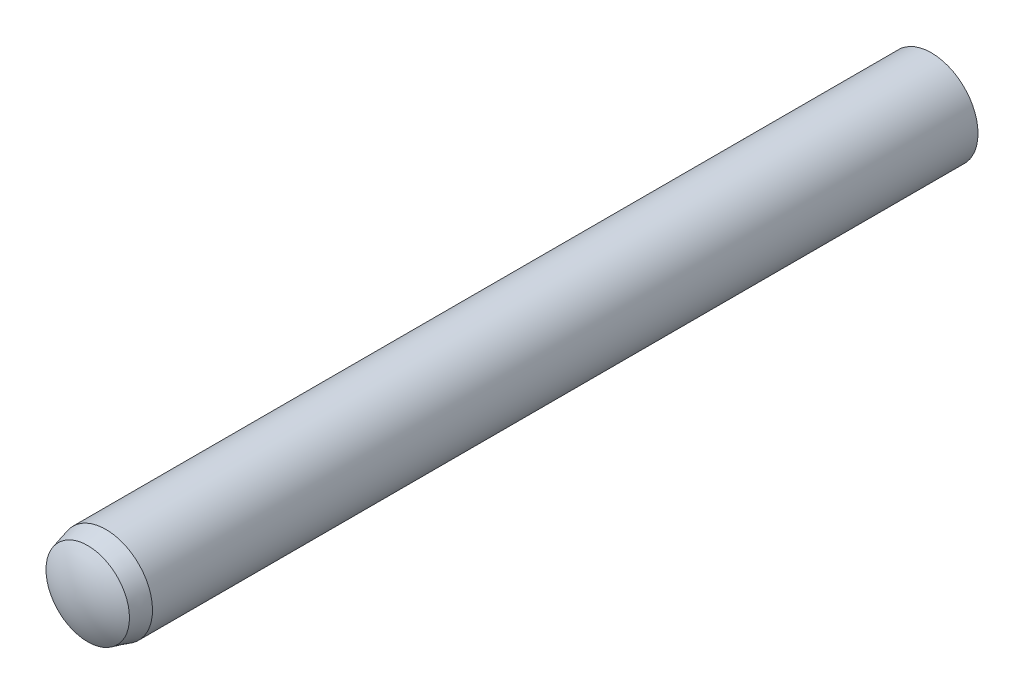
SolidWorks part; units mm, degrees
ref_plane "Front Plane" through (0, 0, 0) normal (0, 0, 1) x (1, 0, 0)
ref_plane "Top Plane" through (0, 0, 0) normal (0, 1, 0) x (1, 0, 0)
ref_plane "Right Plane" through (0, 0, 0) normal (1, 0, 0) x (0, 0, -1)
sketch "Sketch1" plane through (0, 0, 0) normal (0, 0, 1) x (1, 0, 0)
  circle A0 centre (0, 0) radius 1.5
  point P3 (0, 1.5)
  dimension "Diameter" = 3
sketch "Sketch2" plane through (0, 0, 0) normal (1, 0, 0) x (0, 0, -1)
  line L0 (-14, 0) -> (14, 0) construction
  line L1 (-14, 0) -> (-14, 1.5) construction
  line L2 (-14, 1.5) -> (14, 1.5)
  line L3 (14, 1.5) -> (14, 0) construction
  line L4 (-13.61, 1.3432) -> (-13.025, 1.5)
  arc A0 (-14, 0) -> (-13.61, 1.3432) centre (-11.4918, 0) cw
  arc A1 (14, 0) -> (13.55, 1.5) centre (11.275, 0) ccw
  point P2 (0, 0)
  point P11 (-11, 0)
  point P13 (11, 0)
  dimension "Length" = 28
  dimension "D1" = 15
  dimension "D2" = 0.45
  dimension "D3" = 0.975
  dimension "D4" = 0.585
  dimension "D5" = 3
  dimension "D6" = 3
sketch "Sketch3" plane through (0, 0, 0) normal (1, 0, 0) x (0, 0, -1)
  line L0 (-14, 0) -> (14, 0) construction
  line L1 (-13.61, 1.3432) -> (-13.025, 1.5) construction
  line L2 (-14, 0) -> (14, 0)
  line L3 (-13.61, 1.3432) -> (-13.025, 1.5)
  line L4 (-13.025, 1.5) -> (13.55, 1.5)
  arc A0 (14, 0) -> (13.55, 1.5) centre (11.275, 0) ccw construction
  arc A1 (-13.61, 1.3432) -> (-14, 0) centre (-11.4918, 0) ccw construction
  arc A2 (14, 0) -> (13.55, 1.5) centre (11.275, 0) ccw
  arc A3 (-13.61, 1.3432) -> (-14, 0) centre (-11.4918, 0) ccw
revolve "Revolve1" add sketch "Sketch3" angle 360 about L2
sketch "Sketch4" plane through (0, 0, 0) normal (0, 1, 0) x (1, 0, 0)
  point P0 (0, 14)
  point P2 (0, -14)
equation "\"D2@Sketch2\" = \"Diameter@Sketch1\" * .15"
equation "\"D3@Sketch2\" = \"Diameter@Sketch1\" * .325"
equation "\"D4@Sketch2\" = \"D3@Sketch2\" * .6"
equation "\"D5@Sketch2\"=\"Diameter@Sketch1\""
equation "\"D6@Sketch2\"=\"D5@sketch2\""
